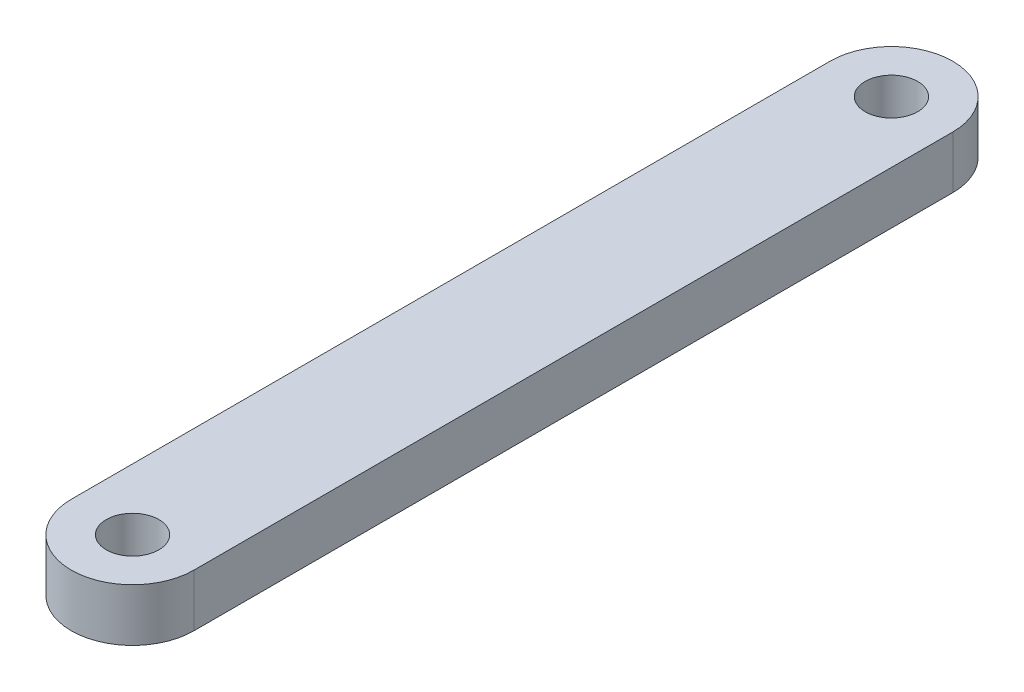
SolidWorks part; units mm, degrees
ref_plane "前视基准面" through (0, 0, 0) normal (0, 0, 1) x (1, 0, 0)
ref_plane "上视基准面" through (0, 0, 0) normal (0, 1, 0) x (1, 0, 0)
ref_plane "右视基准面" through (0, 0, 0) normal (1, 0, 0) x (0, 0, -1)
sketch "草图1" plane through (0, 0, 0) normal (0, 1, 0) x (1, 0, 0)
  line L0 (0, -21.65) -> (0, 21.65) construction
  line L1 (-3.5, -21.65) -> (-3.5, 21.65)
  line L2 (3.5, -21.65) -> (3.5, 21.65)
  arc A0 (-3.5, -21.65) -> (3.5, -21.65) centre (0, -21.65) ccw
  arc A1 (3.5, 21.65) -> (-3.5, 21.65) centre (0, 21.65) ccw
  point P3 (0, 0)
  dimension "D2" = 3.5
  dimension "D1" = 43.3
extrude "凸台-拉伸1" add sketch "草图1" along normal blind 3
sketch "草图2" plane through (0, 3, 0) normal (0, 1, 0) x (1, 0, 0)
  circle A0 centre (0, 21.65) radius 1.5
  circle A2 centre (0, -21.65) radius 1.5
  arc A3 (3.5, 21.65) -> (-3.5, 21.65) centre (0, 21.65) ccw construction
  arc A4 (-3.5, -21.65) -> (3.5, -21.65) centre (0, -21.65) ccw construction
  dimension "D1" = 3
extrude "切除-拉伸1" cut sketch "草图2" against normal blind 3
